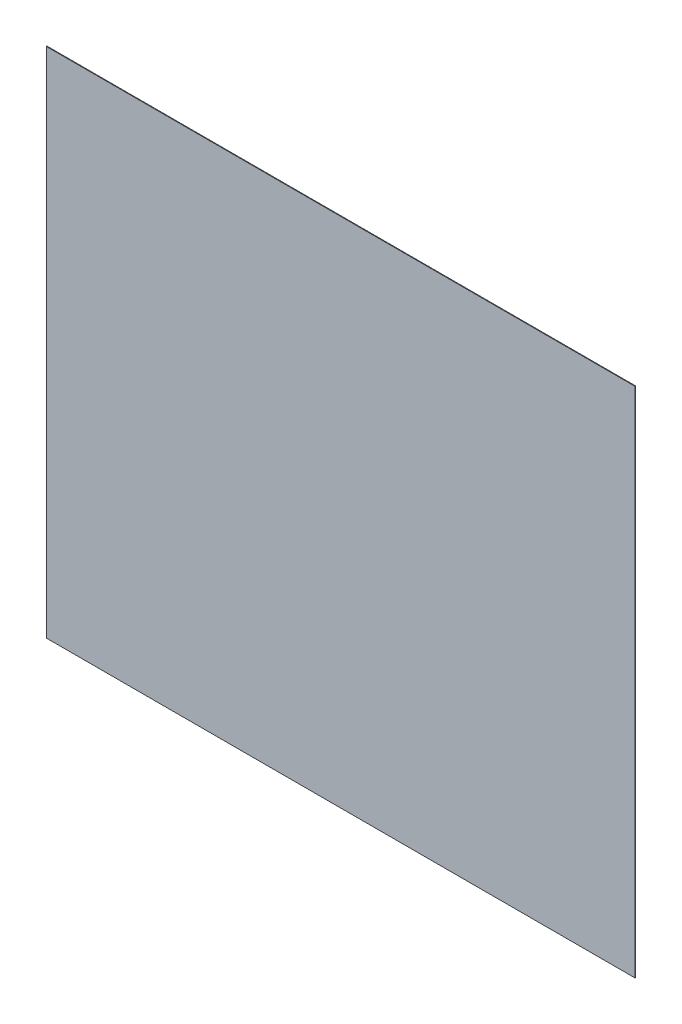
SolidWorks part; units mm, degrees
material "Chrome Stainless Steel"
ref_plane "Front Plane" through (0, 0, 0) normal (0, 0, 1) x (1, 0, 0)
ref_plane "Top Plane" through (0, 0, 0) normal (0, 1, 0) x (1, 0, 0)
ref_plane "Right Plane" through (0, 0, 0) normal (1, 0, 0) x (0, 0, -1)
sketch "Sketch1" plane through (0, 0, 0) normal (0, 0, 1) x (1, 0, 0)
  line L1 (-159.1526, 0) -> (750, 0)
  line L2 (-159.1526, 0) -> (-159.1526, 791.14)
  line L3 (-159.1526, 791.14) -> (750, 791.14)
  line L4 (750, 0) -> (750, 791.14)
extrude "Boss-Extrude1" add sketch "Sketch1" along normal blind 1
